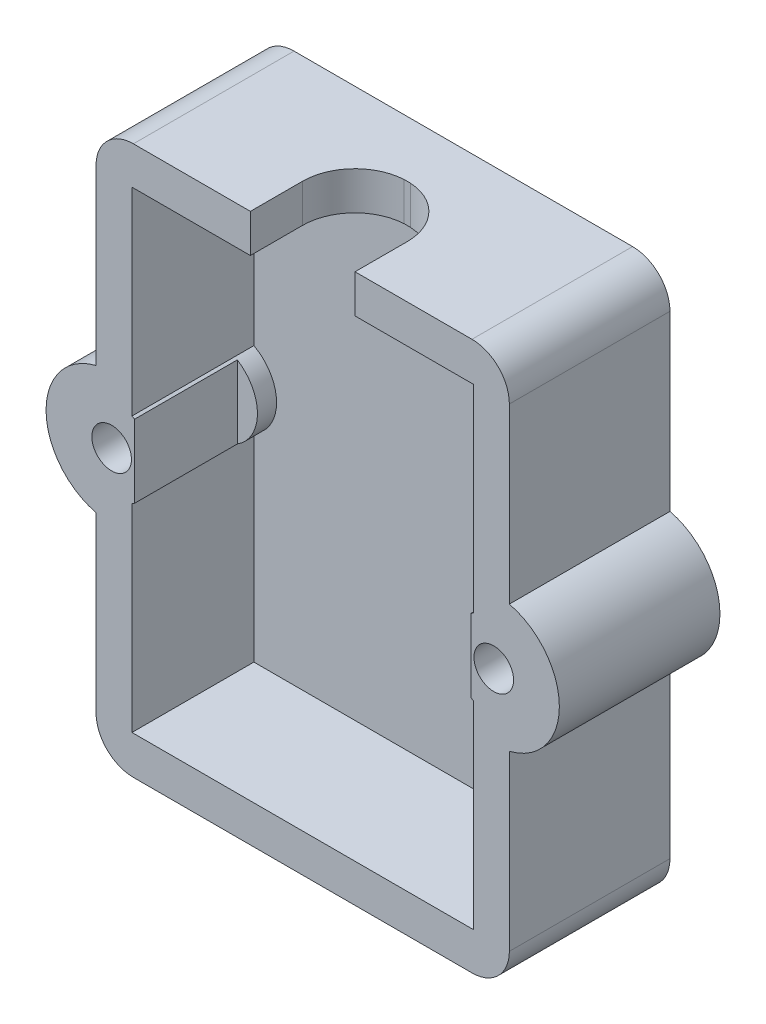
SolidWorks part; units mm, degrees
ref_plane "Front Plane" through (0, 0, 0) normal (0, 0, 1) x (1, 0, 0)
ref_plane "Top Plane" through (0, 0, 0) normal (0, 1, 0) x (1, 0, 0)
ref_plane "Right Plane" through (0, 0, 0) normal (1, 0, 0) x (0, 0, -1)
sketch "Sketch1" plane through (0, 0, 0) normal (0, 0, 1) x (1, 0, 0)
  line L0 (0, 0) -> (0, 25.5) construction
  line L1 (-15, 25.5) -> (15, 25.5) construction
  line L2 (-10.225, 13.5) -> (0, 13.5) construction
  line L3 (0, 13.5) -> (10.225, 13.5) construction
  line L4 (-11.06, 0.8164) -> (-11.06, 10.0908)
  line L9 (0, 25.1336) -> (0, -0.2336) construction
  line L10 (-9.06, 13.5) -> (9.06, 13.5) construction
  line L11 (-9.06, 28.1836) -> (9.06, 28.1836)
  line L12 (11.06, 0.8164) -> (11.06, 10.0908)
  line L13 (-9.06, -1.1836) -> (9.06, -1.1836)
  line L18 (-11.06, 16.9092) -> (-11.06, 26.1836)
  line L20 (11.06, 16.9092) -> (11.06, 26.1836)
  arc A2 (11.06, 16.9092) -> (11.06, 10.0908) centre (10.225, 13.5) cw
  arc A3 (-11.06, 16.9092) -> (-11.06, 10.0908) centre (-10.225, 13.5) ccw
  arc A4 (-11.06, 0.8164) -> (-9.06, -1.1836) centre (-9.06, 0.8164) ccw
  arc A5 (11.06, 0.8164) -> (9.06, -1.1836) centre (9.06, 0.8164) cw
  arc A6 (9.06, 28.1836) -> (11.06, 26.1836) centre (9.06, 26.1836) cw
  arc A8 (-11.06, 26.1836) -> (-9.06, 28.1836) centre (-9.06, 26.1836) cw
  point P11 (-13.735, 13.5)
  dimension "D1" = 2
  dimension "D2" = 6.8185
  dimension "D3" = 29.3672
extrude "Boss-Extrude2" add sketch "Sketch1" along normal blind 8.595 contours L11 A6 L20 A2 L12 A5 L13 A4 L4 A3 L18 A8
sketch "Sketch2" plane through (0, 0, 8.595) normal (0, 0, 1) x (1, 0, 0)
  line L6 (0, -1.1836) -> (0, 28.1836) construction
  line L7 (-9.06, -1.1836) -> (9.06, -1.1836) construction
  line L8 (-9.06, 28.1836) -> (9.06, 28.1836) construction
  line L9 (13.735, 13.5) -> (-13.735, 13.5) construction
  line L10 (0, -0.2133) -> (0, 25.2203) construction
  line L11 (-10.5637, 13.5) -> (9.8863, 13.5) construction
  line L12 (-9.1375, 15.5286) -> (-9.1375, 26.1364)
  line L13 (-9.1375, 0.8614) -> (9.1375, 0.8614)
  line L14 (-9.1375, 0.8614) -> (-9.1375, 11.4714)
  line L15 (-9.1375, 26.1364) -> (9.1375, 26.1364)
  line L16 (9.1375, 0.8614) -> (9.1375, 11.4714)
  line L17 (0, 26.1364) -> (0, 0.8614) construction
  line L18 (-9.075, 13.5) -> (9.075, 13.5) construction
  line L19 (9.1375, 15.5286) -> (9.1375, 26.1364)
  line L21 (-9.06, -1.1836) -> (9.06, -1.1836) construction
  arc A2 (11.06, 10.0908) -> (11.06, 16.9092) centre (10.225, 13.5) ccw construction
  arc A3 (-11.06, 16.9092) -> (-11.06, 10.0908) centre (-10.225, 13.5) ccw construction
  arc A4 (-9.1375, 11.4714) -> (-9.1375, 15.5286) centre (-10.225, 13.5) ccw
  arc A5 (9.1375, 11.4714) -> (9.1375, 15.5286) centre (10.225, 13.5) cw
  point P6 (0, 13.5)
  dimension "D1" = 25.275
  dimension "D2" = 18.275
  dimension "D4" = 2.045
sketch "Sketch5" plane through (0, 0, 8.595) normal (0, 0, 1) x (1, 0, 0)
  line L0 (0, 28.1836) -> (0, -1.1836) construction
  line L1 (-11.06, 0.8164) -> (-11.06, 10.0908) construction
  line L2 (-9.06, -1.1836) -> (9.06, -1.1836) construction
  circle A0 centre (-10.225, 13.5) radius 1.06
  circle A1 centre (10.225, 13.5) radius 1.06
  dimension "D1" = 20.12
  dimension "D3" = 2.12
  dimension "D2" = 11.2744
  dimension "D4" = 0.835
  dimension "D5" = 14.6836
extrude "Cut-Extrude3" cut sketch "Sketch5" against normal up to next
extrude "Cut-Extrude4" cut sketch "Sketch2" against normal blind 6.525
sketch "Sketch3" plane through (0, 28.1836, 0) normal (0, 1, 0) x (1, 0, 0)
  line L0 (0, 0) -> (0, -8.595) construction
  line L1 (-9.06, -8.595) -> (9.06, -8.595) construction
  line L2 (11.06, -4.2975) -> (-11.06, -4.2975) construction
  line L3 (11.06, -8.595) -> (11.06, 0) construction
  line L4 (-11.06, -8.595) -> (-11.06, 0) construction
  line L5 (-9.06, 0) -> (9.06, 0) construction
  line L7 (-0.1673, -3.005) -> (0.1673, -3.005)
  line L8 (-2.8, -5.8) -> (-2.8, -8.595)
  line L9 (-2.8, -8.595) -> (2.8, -8.595)
  line L10 (2.8, -5.8) -> (2.8, -8.595)
  line L11 (0, -8.595) -> (0, -3.005) construction
  line L12 (-2.8, -5.8) -> (2.8, -5.8) construction
  arc A0 (2.8, -5.8) -> (-2.8, -5.8) centre (0, -5.8) ccw
  arc A1 (-0.1673, -8.595) -> (0.1673, -8.595) centre (0, -5.8) ccw
  line M4 (-9.06, -8.595) -> (9.06, -8.595)
  dimension "D1" = 5.8
extrude "Cut-Extrude2" cut sketch "Sketch3" against normal up to next contours L10 A0 L7 L8 L9 M4
sketch "Sketch7" plane through (0, 0, 8.595) normal (0, 0, 1) x (1, 0, 0)
  line L0 (-9, 1.2233) -> (9, 1.2233)
  line L1 (-9, 1.2233) -> (-9, 25.8733)
  line L2 (-9, 25.8733) -> (9, 25.8733)
  line L3 (9, 1.2233) -> (9, 25.8733)
  line L6 (-9.1375, 0.8614) -> (9.1375, 0.8614) construction
  point P4 (0, 1.2233)
  dimension "D1" = 18
  dimension "D2" = 0.3619
  dimension "D3" = 25.0119
extrude "Cut-Extrude6" cut sketch "Sketch7" against normal blind 5.5
